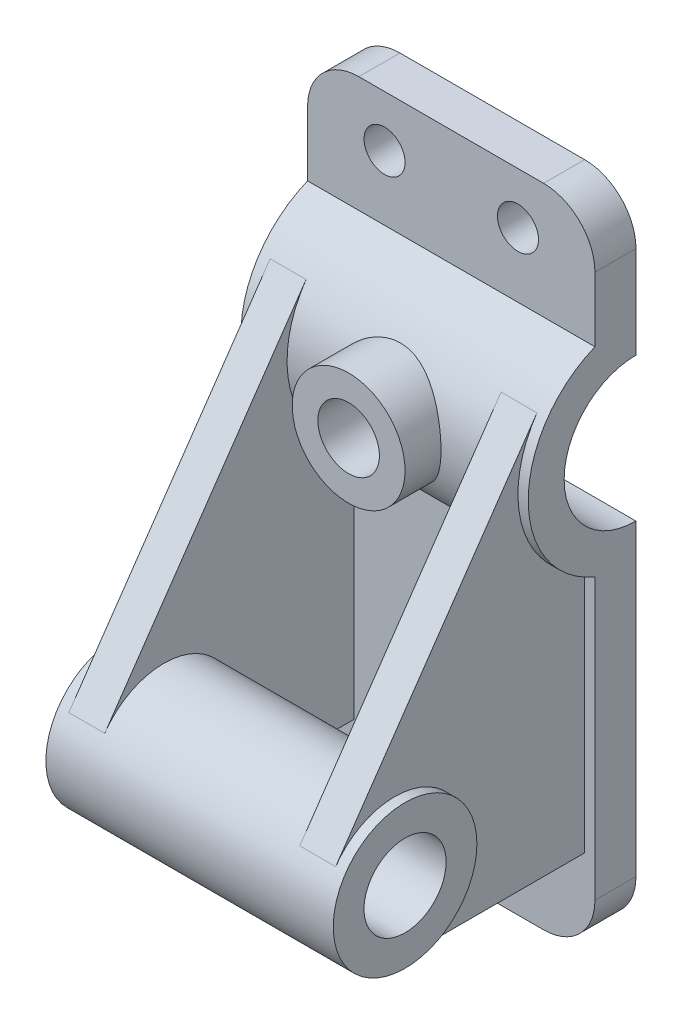
SolidWorks part; units mm, degrees
ref_plane "Front Plane" through (0, 0, 0) normal (1, 0, 0) x (0, 1, 0)
ref_plane "Top Plane" through (0, 0, 0) normal (0, 0, 1) x (0, 1, 0)
ref_plane "Right Plane" through (0, 0, 0) normal (0, 1, 0) x (-1, 0, 0)
sketch "Sketch1" plane through (0, 0, 0) normal (1, 0, 0) x (0, 1, 0)
  line L0 (-118.9401, 0) -> (0, 0) construction
  line L1 (42, 0) -> (14, 0)
  line L2 (14, 0) -> (96.3973, 0) construction
  line L3 (0, 30.1704) -> (0, -29.4354) construction
  line L4 (-84, 0) -> (-14, 0)
  line L5 (-84, 0) -> (-84, 8)
  line L6 (-84, 8) -> (-19.4165, 8)
  line L7 (42, 8) -> (42, 0)
  line L9 (19.4165, 8) -> (42, 8)
  arc A0 (14, 0) -> (-14, 0) centre (0, 0) ccw
  arc A1 (19.4165, 8) -> (-19.4165, 8) centre (0, 0) ccw
  dimension "D1" = 14
  dimension "D2" = 21
  dimension "D3" = 42
  dimension "D4" = 126
  dimension "D5" = 8
extrude "Boss-Extrude1" add sketch "Sketch1" along normal mid plane 56
fillet "Fillet1" radius 10 4 edges at (-28, -84, 4) (28, -84, 4) (-28, 42, 4) (28, 42, 4)
sketch "Sketch2" plane through (0, 0, 0) normal (1, 0, 0) x (0, 1, 0)
  line L0 (-67, 45) -> (-67, 8)
  line L1 (-19.4165, 8) -> (-74, 8) construction
  line L2 (-39, 45) -> (-39, 8)
  line L3 (-74, 0) -> (-14, 0) construction
  line L4 (-67, 8) -> (-19.4165, 8)
  circle A0 centre (-53, 45) radius 8
  circle A1 centre (-53, 45) radius 14
  arc A3 (-19.4165, 8) -> (11.9111, 17.2953) centre (0, 0) cw
  dimension "D2" = 28
  dimension "D3" = 16
  dimension "D1" = 45
  dimension "D4" = 53
extrude "Boss-Extrude3" add sketch "Sketch2" along normal mid plane 56 separate body contours A1 A0
ref_plane "Plane1" through (19, 0, 0) normal (1, 0, 0) x (0, 1, 0)
sketch "Sketch3" plane through (19, 0, 0) normal (1, 0, 0) x (0, 1, 0)
  line L0 (-67, 45) -> (-67, 8)
  line L1 (-19.4165, 8) -> (-74, 8) construction
  line L2 (-67, 8) -> (-19.4165, 8)
  line L3 (32, 8) -> (19.4165, 8) construction
  line L4 (-45.0593, 56.5302) -> (11.9111, 17.2953)
  circle A0 centre (-53, 45) radius 14
  arc A1 (-19.4165, 8) -> (19.4165, 8) centre (0, 0) cw
  circle A2 centre (-53, 45) radius 14 construction
extrude "Boss-Extrude4" add sketch "Sketch3" along normal blind 7 contours L2 A1 L4 A0 L0
mirror "Mirror1" about plane through (0, 0, 0) normal (1, 0, 0) of "Boss-Extrude4"
ref_plane "Plane2" through (0, 0, 28) normal (0, 0, 1) x (1, 0, 0)
sketch "Sketch5" plane through (0, 0, 28) normal (0, 0, 1) x (1, 0, 0)
  circle A0 centre (0, 0) radius 6
  circle A1 centre (0, 0) radius 11
  dimension "D1" = 12
  dimension "D2" = 22
extrude "Boss-Extrude5" add sketch "Sketch5" against normal up to surface (7 mm away)
sketch "Sketch6" plane through (0, 0, 28) normal (0, 0, 1) x (1, 0, 0)
  circle A0 centre (0, 0) radius 6
extrude "Cut-Extrude1" cut sketch "Sketch6" against normal through all both and the other way through all
sketch "Sketch8" plane through (0, 0, 8) normal (0, 0, 1) x (1, 0, 0)
  line L0 (0, 0) -> (0, 8.3638) construction
  circle A0 centre (-13, 32) radius 4
  circle A1 centre (13, 32) radius 4
  dimension "D1" = 26
  dimension "D2" = 8
extrude "Cut-Extrude2" cut sketch "Sketch8" against normal through all both and the other way through all
sketch "Sketch9" plane through (0, 0, 8) normal (0, 0, 1) x (1, 0, 0)
  line L0 (0, 0) -> (0, -29.0761) construction
  circle A0 centre (-13, -74) radius 4
  circle A1 centre (13, -74) radius 4
  point P7 (0, 0)
  dimension "D1" = 26
  dimension "D2" = 8
extrude "Cut-Extrude3" cut sketch "Sketch9" against normal through all both and the other way through all
